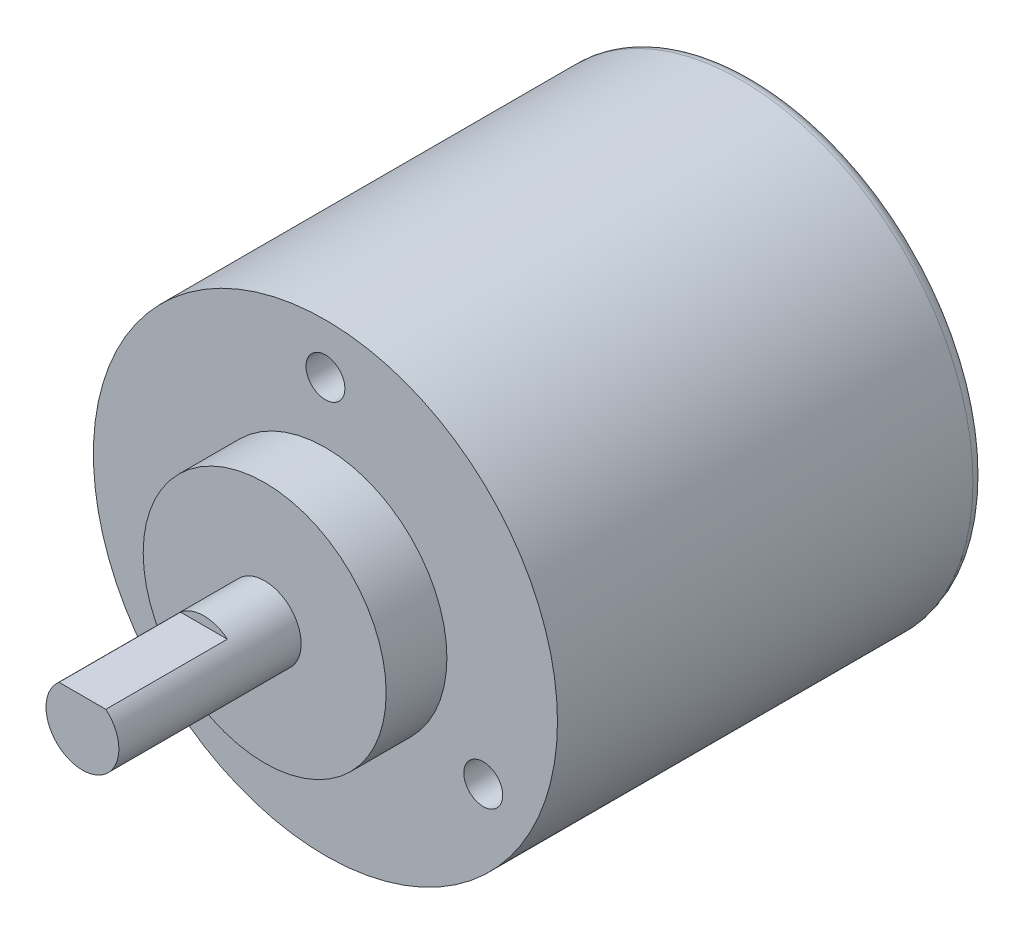
SolidWorks part; units mm, degrees
ref_plane "前视基准面" through (0, 0, 0) normal (0, 0, 1) x (1, 0, 0)
ref_plane "上视基准面" through (0, 0, 0) normal (0, 1, 0) x (1, 0, 0)
ref_plane "右视基准面" through (0, 0, 0) normal (1, 0, 0) x (0, 0, -1)
sketch "草图1" plane through (0, 0, 0) normal (0, 0, 1) x (1, 0, 0)
  circle A0 centre (0, 0) radius 19.1
  point P13 (0, 0)
  dimension "D2" = 38.2
extrude "凸台-拉伸1" add sketch "草图1" along normal blind 35.2
sketch "草图2" plane through (0, 0, 35.2) normal (0, 0, 1) x (1, 0, 0)
  circle A0 centre (0, 0) radius 10
  circle A1 centre (0, 14.1337) radius 1.4716
  dimension "D1" = 20
extrude "凸台-拉伸2" add sketch "草图2" along normal blind 5 contours A0
sketch "草图4" plane through (0, 0, 35.2) normal (0, 0, 1) x (1, 0, 0)
  circle A0 centre (0, 15) radius 1.6
  circle A1 centre (0, 0) radius 10 construction
  circle A4 centre (12.9904, -7.5) radius 1.6
  circle A5 centre (-12.9904, -7.5) radius 1.6
  point P10 (0, 0)
  point P12 (0, 0)
  dimension "D1" = 3.2
  dimension "D2" = 15
  dimension "D3" = 3
extrude "切除-拉伸1" cut sketch "草图4" against normal blind 5
sketch "草图5" plane through (0, 0, 40.2) normal (0, 0, 1) x (1, 0, 0)
  circle A0 centre (0, 0) radius 3
  dimension "D1" = 6
extrude "凸台-拉伸3" add sketch "草图5" along normal blind 15
sketch "草图6" plane through (0, 0, 55.2) normal (0, 0, 1) x (1, 0, 0)
  line L0 (-1.9261, 2.3) -> (1.9261, 2.3)
  circle A0 centre (0, 0) radius 3 construction
  arc A1 (1.9261, 2.3) -> (-1.9261, 2.3) centre (0, 0) ccw
  dimension "D1" = 2.3
extrude "切除-拉伸2" cut sketch "草图6" against normal blind 10
fillet "圆角1" radius 1 1 edges at (19.1, 0, 0)
